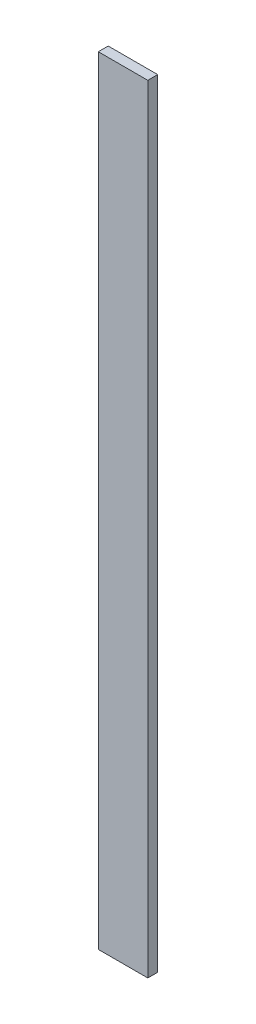
SolidWorks part; units mm, degrees
ref_plane "前视基准面" through (0, 0, 0) normal (0, 0, 1) x (1, 0, 0)
ref_plane "上视基准面" through (0, 0, 0) normal (0, 1, 0) x (1, 0, 0)
ref_plane "右视基准面" through (0, 0, 0) normal (1, 0, 0) x (0, 0, -1)
sketch "草图2" plane through (0, 0, 0) normal (0, 0, 1) x (1, 0, 0)
  line L33 (196.4884, -200.8866) -> (186.4884, -200.8866)
  line L34 (186.4884, -200.8866) -> (186.4884, -43.8866)
  line L35 (186.4884, -43.8866) -> (196.4884, -43.8866)
  line L36 (196.4884, -43.8866) -> (196.4884, -200.8866)
extrude "凸台-拉伸1" add sketch "草图2" along normal blind 2
